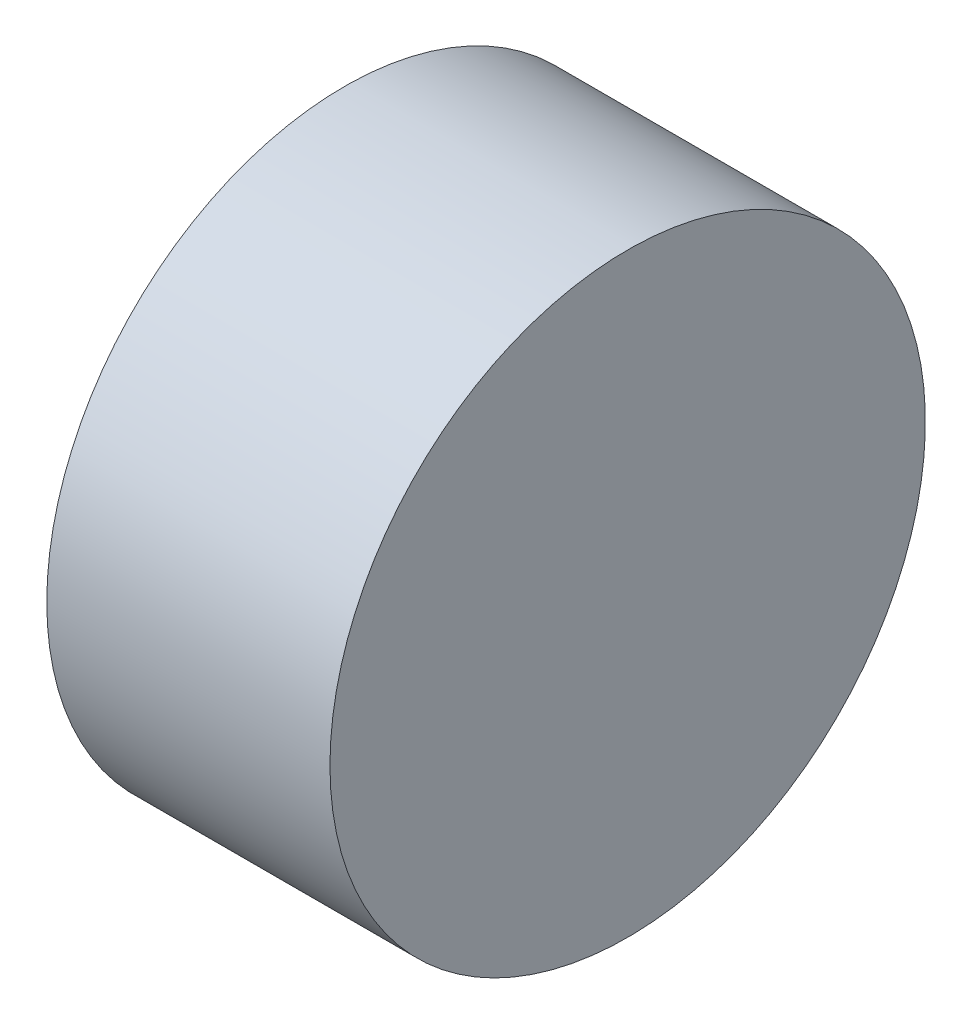
SolidWorks part; units mm, degrees
ref_plane "Front Plane" through (0, 0, 0) normal (0, 0, 1) x (1, 0, 0)
ref_plane "Top Plane" through (0, 0, 0) normal (0, 1, 0) x (1, 0, 0)
ref_plane "Right Plane" through (0, 0, 0) normal (1, 0, 0) x (0, 0, -1)
sketch "Sketch1" plane through (0, 0, 0) normal (0, 0, 1) x (1, 0, 0)
  line L1 (3.1273, 0.653) -> (4.5241, 0.653)
  line L3 (4.5241, 6.6877) -> (4.5241, 0.653)
  line L8 (-1.2155, 6.6877) -> (4.5241, 6.6877)
  line L10 (-1.2155, 3.6037) -> (-1.2155, 6.6877)
  arc A1 (-1.2155, 3.6037) -> (3.1273, 0.653) centre (-0.0752, 0.6108) cw
  point P19 (4.5241, 0.653)
other "Pen Sketch1" parameters "D7"=3.2028, "D1"=6.6877, "D2"=3.084, "D3"=4.5241, "D4"=1.778, "D5"=1.964, "D6"=1.964, "D8"=0.6108
ref_axis "Axis1" through (3.1273, 0.653, 0) along (1, 0, 0)
revolve "Revolve2" add sketch "Sketch1" angle 360 about axis through (3.1273, 0.653, 0) along (1, 0, 0)
